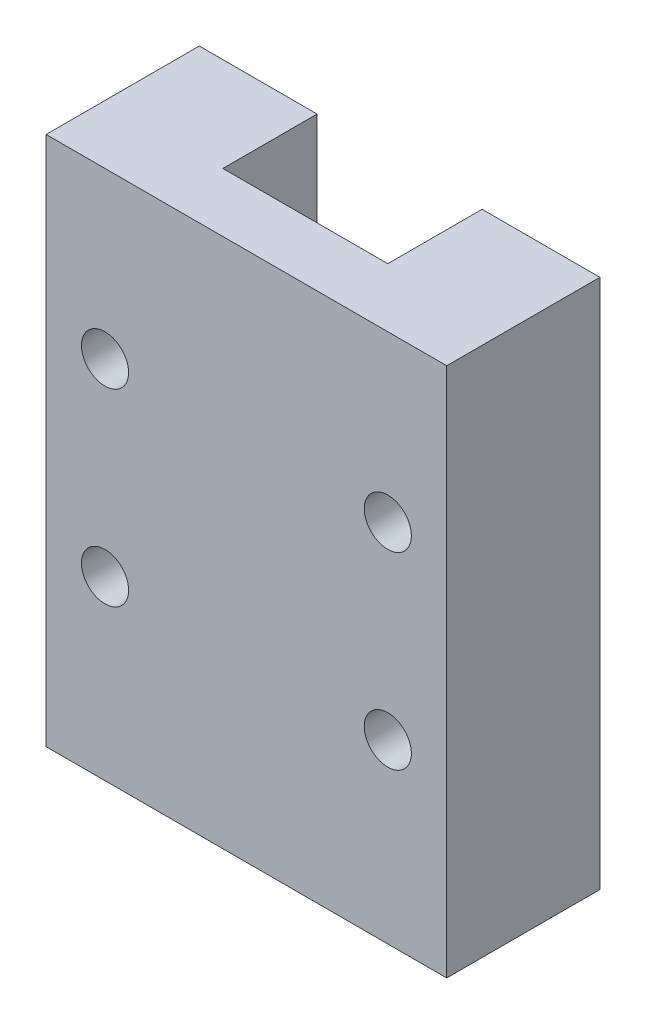
SolidWorks part; units mm, degrees
ref_plane "Front Plane" through (0, 0, 0) normal (0, 0, 1) x (1, 0, 0)
ref_plane "Top Plane" through (0, 0, 0) normal (0, 1, 0) x (1, 0, 0)
ref_plane "Right Plane" through (0, 0, 0) normal (1, 0, 0) x (0, 0, -1)
sketch "草图1" plane through (0, 0, 0) normal (0, 1, 0) x (1, 0, 0)
  line L0 (-3.5, -0.75) -> (3.5, -0.75)
  line L1 (-8.5, 3.25) -> (-3.5, 3.25)
  line L2 (-8.5, 3.25) -> (-8.5, -3.25)
  line L3 (-8.5, -3.25) -> (8.5, -3.25)
  line L4 (8.5, 3.25) -> (8.5, -3.25)
  line L5 (-8.5, 3.25) -> (8.5, -3.25) construction
  line L6 (-8.5, -3.25) -> (8.5, 3.25) construction
  line L7 (3.5, -0.75) -> (3.5, 3.25)
  line L8 (-3.5, -0.75) -> (-3.5, 3.25)
  line L9 (3.5, 3.25) -> (8.5, 3.25)
  line L15 (-6.1966, 2.3693) -> (6.1966, -2.3693) construction
  line L16 (-6.1966, -2.3693) -> (6.1966, 2.3693) construction
  point P0 (0, 0)
  point P8 (0, 0)
  dimension "D1" = 17
  dimension "D2" = 6.5
  dimension "D3" = 2.5
  dimension "D4" = 3.5
  dimension "D5" = 3.5
extrude "凸台-拉伸1" add sketch "草图1" along normal blind 22.5
sketch "草图2" plane through (0, 0, 3.25) normal (0, 0, 1) x (1, 0, 0)
  line L0 (0, 0) -> (0, 22.5) construction
  line L1 (-8.5, 22.5) -> (8.5, 22.5) construction
  circle A0 centre (-6, 15.5) radius 1
  circle A1 centre (-6, 7.5) radius 1
  circle A2 centre (6, 7.5) radius 1
  circle A3 centre (6, 15.5) radius 1
  dimension "D1" = 2
  dimension "D2" = 2
  dimension "D3" = 6
  dimension "D4" = 7
  dimension "D5" = 8
extrude "切除-拉伸1" cut sketch "草图2" against normal blind 4
